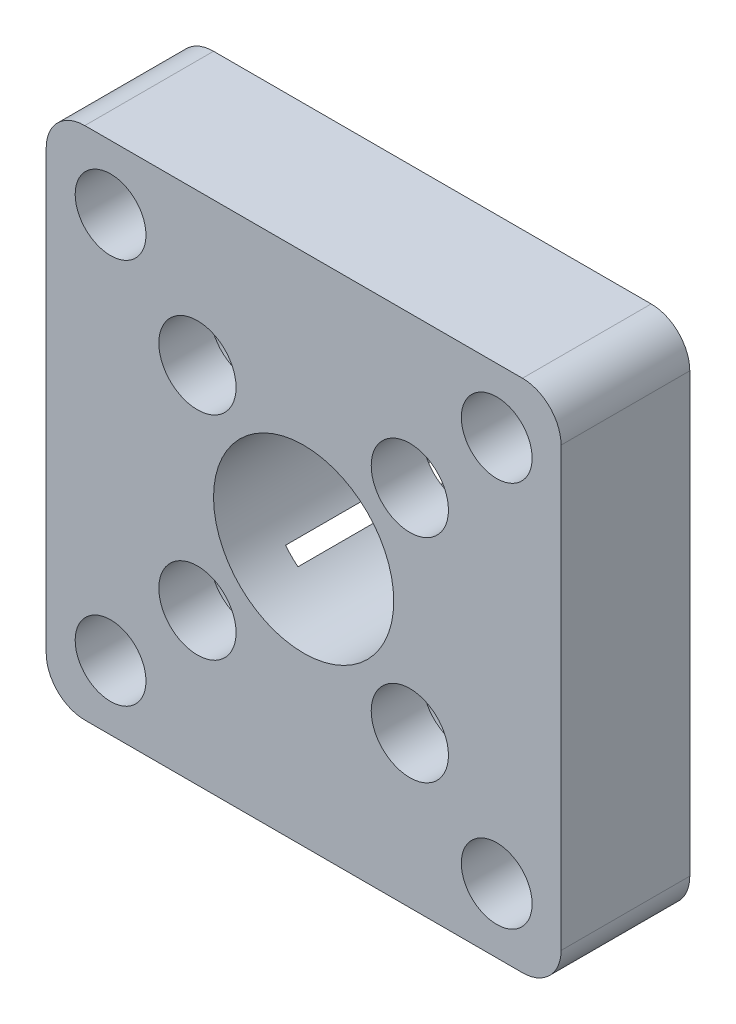
SolidWorks part; units mm, degrees
ref_plane "前视基准面" through (0, 0, 0) normal (0, 0, 1) x (1, 0, 0)
ref_plane "上视基准面" through (0, 0, 0) normal (0, 1, 0) x (1, 0, 0)
ref_plane "右视基准面" through (0, 0, 0) normal (1, 0, 0) x (0, 0, -1)
sketch "草图1" plane through (0, 0, 0) normal (0, 0, 1) x (1, 0, 0)
  line L69 (1187.7902, 994.6271) -> (1233.6204, 994.6271) construction
  line L70 (1210.5085, 1016.7989) -> (1210.5085, 973.3273) construction
  line L92 (1212.9463, 1002.8771) -> (1224.0992, 1002.8771) construction
  line L93 (1218.7585, 1008.3744) -> (1218.7585, 997.6105) construction
  line L94 (1202.2585, 1008.3744) -> (1202.2585, 997.6105) construction
  line L95 (1196.4463, 1002.8771) -> (1207.5992, 1002.8771) construction
  line L96 (1202.2585, 991.8744) -> (1202.2585, 981.1105) construction
  line L97 (1196.4463, 986.3771) -> (1207.5992, 986.3771) construction
  line L98 (1218.7585, 991.8744) -> (1218.7585, 981.1105) construction
  line L99 (1212.9463, 986.3771) -> (1224.0992, 986.3771) construction
  line L100 (1225.5085, 985.1244) -> (1225.5085, 974.3605) construction
  line L101 (1219.6963, 979.6271) -> (1230.8492, 979.6271) construction
  line L102 (1195.5085, 985.1244) -> (1195.5085, 974.3605) construction
  line L103 (1189.6963, 979.6271) -> (1200.8492, 979.6271) construction
  line L104 (1195.5085, 1015.1244) -> (1195.5085, 1004.3605) construction
  line L105 (1189.6963, 1009.6271) -> (1200.8492, 1009.6271) construction
  line L106 (1225.5085, 1015.1244) -> (1225.5085, 1004.3605) construction
  line L107 (1219.6963, 1009.6271) -> (1230.8492, 1009.6271) construction
  line L115 (1190.5085, 1011.6271) -> (1190.5085, 977.6271)
  line L116 (1193.5085, 974.6271) -> (1227.5085, 974.6271)
  line L117 (1230.5085, 977.6271) -> (1230.5085, 1011.6271)
  line L118 (1227.5085, 1014.6271) -> (1193.5085, 1014.6271)
  arc A4 (1215.9175, 999.0704) -> (1214.9517, 1000.0362) centre (1218.7585, 1002.8771) ccw construction
  circle A5 centre (1218.7585, 1002.8771) radius 3
  circle A6 centre (1218.7585, 986.3771) radius 3
  arc A7 (1214.9517, 989.2181) -> (1215.9175, 990.1839) centre (1218.7585, 986.3771) ccw construction
  circle A8 centre (1202.2585, 1002.8771) radius 3
  arc A9 (1206.0653, 1000.0362) -> (1205.0995, 999.0704) centre (1202.2585, 1002.8771) ccw construction
  arc A10 (1205.0995, 990.1839) -> (1206.0653, 989.2181) centre (1202.2585, 986.3771) ccw construction
  circle A11 centre (1202.2585, 986.3771) radius 3
  circle A12 centre (1210.5085, 994.6271) radius 7
  arc A13 (1193.5085, 1014.6271) -> (1190.5085, 1011.6271) centre (1193.5085, 1011.6271) ccw
  arc A14 (1190.5085, 977.6271) -> (1193.5085, 974.6271) centre (1193.5085, 977.6271) ccw
  arc A15 (1227.5085, 974.6271) -> (1230.5085, 977.6271) centre (1227.5085, 977.6271) ccw
  arc A16 (1230.5085, 1011.6271) -> (1227.5085, 1014.6271) centre (1227.5085, 1011.6271) ccw
  circle A17 centre (1195.5085, 979.6271) radius 4.75 construction
  circle A18 centre (1225.5085, 979.6271) radius 4.75 construction
  circle A19 centre (1225.5085, 1009.6271) radius 4.75 construction
  circle A20 centre (1195.5085, 1009.6271) radius 4.75 construction
  circle A21 centre (1195.5085, 1009.6271) radius 2.75
  circle A22 centre (1225.5085, 1009.6271) radius 2.75
  circle A23 centre (1225.5085, 979.6271) radius 2.75
  circle A24 centre (1195.5085, 979.6271) radius 2.75
  dimension "D1" = 30
  dimension "D2" = 30
extrude "拉伸1" add sketch "草图1" along normal blind 10
sketch "草图2" plane through (0, 0, 0) normal (0, 0, -1) x (-1, 0, 0)
  circle A0 centre (-1225.5085, 1009.6271) radius 4.75
  circle A2 centre (-1195.5085, 1009.6271) radius 4.75
  circle A3 centre (-1225.5085, 979.6271) radius 4.75
  circle A4 centre (-1195.5085, 979.6271) radius 4.75
  circle A5 centre (-1218.7585, 1002.8771) radius 4.75
  circle A6 centre (-1202.2585, 1002.8771) radius 4.75
  circle A7 centre (-1218.7585, 986.3771) radius 4.75
  circle A8 centre (-1202.2585, 986.3771) radius 4.75
  dimension "D1" = 9.5
  dimension "D2" = 9.5
extrude "拉伸2" cut sketch "草图2" against normal blind 6
